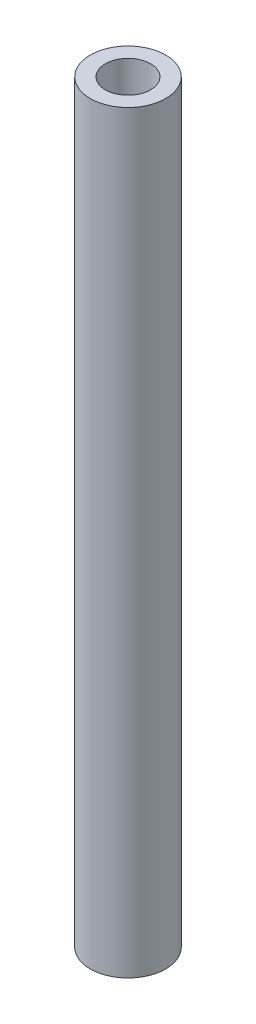
SolidWorks part; units mm, degrees
ref_plane "Front Plane" through (0, 0, 0) normal (0, 0, 1) x (1, 0, 0)
ref_plane "Top Plane" through (0, 0, 0) normal (0, 1, 0) x (1, 0, 0)
ref_plane "Right Plane" through (0, 0, 0) normal (1, 0, 0) x (0, 0, -1)
sketch "Sketch1" plane through (0, 0, 0) normal (0, 1, 0) x (1, 0, 0)
  circle A0 centre (0, 0) radius 2.5
  dimension "D1" = 5
extrude "Boss-Extrude1" add sketch "Sketch1" along normal blind 50
hole_wizard "#31 (0.12) Diameter Hole2" positions "Sketch5" profile "Sketch4" hole size "#31" standard "ANSI Inch"
sketch "Sketch5" plane through (0, 50, 0) normal (0, 1, 0) x (1, 0, 0)
  point P0 (0, 0)
sketch "Sketch4" plane through (0, 50, 0) normal (1, 0, 0) x (0, 0, 1)
  line L0 (0, 0) -> (0, 10.9013)
  line L1 (0, 10.9013) -> (1.5, 10)
  line L2 (1.5, 10) -> (1.5, 0)
  line L5 (1.5, 0) -> (0, 0)
  line L10 (0, 10.9013) -> (-1.5, 10) construction
  line L11 (0, -6.35) -> (0, 107.95) construction
  dimension "Hole Dia." = 3
  dimension "Hole Depth" = 10
  dimension "Drill Angle" = 118
